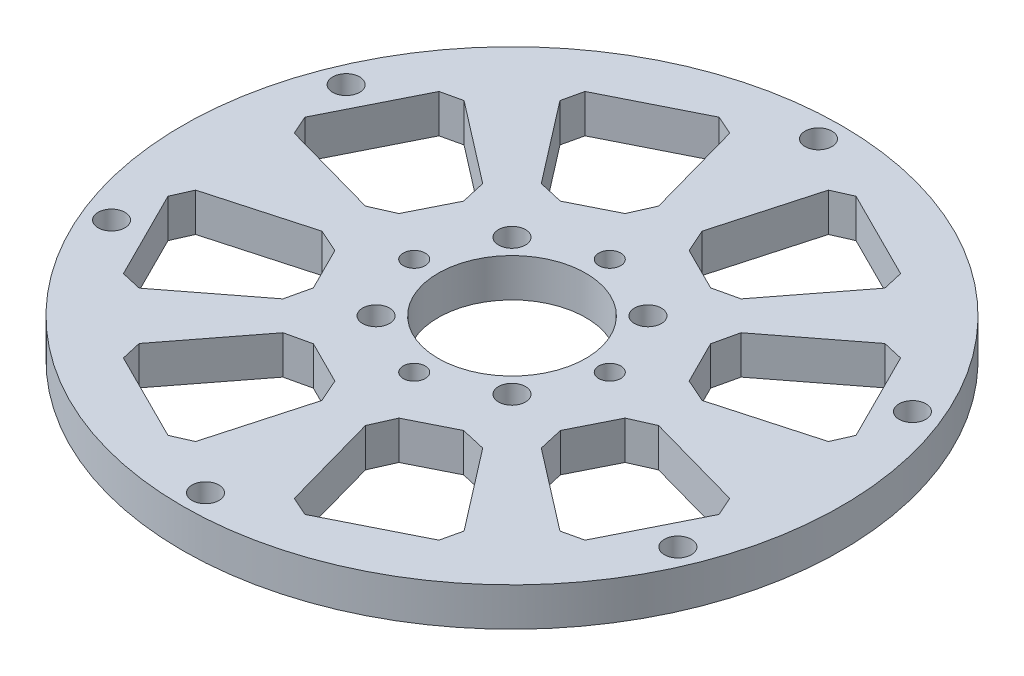
SolidWorks part; units mm, degrees
ref_plane "Front Plane" through (0, 0, 0) normal (0, 0, 1) x (1, 0, 0)
ref_plane "Top Plane" through (0, 0, 0) normal (0, 1, 0) x (1, 0, 0)
ref_plane "Right Plane" through (0, 0, 0) normal (1, 0, 0) x (0, 0, -1)
sketch "Sketch1" plane through (0, 0, 0) normal (0, 1, 0) x (1, 0, 0)
  circle A0 centre (0, 0) radius 60
  dimension "D1" = 120
extrude "Boss-Extrude1" add sketch "Sketch1" along normal blind 7
sketch "Sketch5" plane through (0, 0, 0) normal (0, 1, 0) x (1, 0, 0)
  line L0 (-82.4479, 0) -> (103.3295, 0) construction
  line L1 (0, 67.0321) -> (0, -75.2071) construction
  line L2 (0, 0) -> (-68.1881, 68.1881) construction
  line L3 (-12.4689, 50.1671) -> (-28.7242, 42.0224)
  line L4 (-29.5753, 38.302) -> (-18.1867, 23.5207)
  line L5 (-13.6736, 22.4881) -> (-5.8319, 26.4172)
  line L6 (-3.9571, 30.6504) -> (-8.9793, 48.6217)
  line L7 (-22.4881, 13.6736) -> (-26.4172, 5.8319)
  line L8 (-30.6504, 3.9571) -> (-48.6217, 8.9793)
  line L9 (-38.302, 29.5753) -> (-23.5207, 18.1867)
  line L10 (-50.1671, 12.4689) -> (-42.0224, 28.7242)
  line L11 (22.4881, 13.6736) -> (26.4172, 5.8319)
  line L12 (38.302, 29.5753) -> (23.5207, 18.1867)
  line L13 (50.1671, 12.4689) -> (42.0224, 28.7242)
  line L14 (30.6504, 3.9571) -> (48.6217, 8.9793)
  line L15 (13.6736, 22.4881) -> (5.8319, 26.4172)
  line L16 (29.5753, 38.302) -> (18.1867, 23.5207)
  line L17 (3.9571, 30.6504) -> (8.9793, 48.6217)
  line L18 (12.4689, 50.1671) -> (28.7242, 42.0224)
  line L19 (22.4881, -13.6736) -> (26.4172, -5.8319)
  line L20 (30.6504, -3.9571) -> (48.6217, -8.9793)
  line L21 (50.1671, -12.4689) -> (42.0224, -28.7242)
  line L22 (38.302, -29.5753) -> (23.5207, -18.1867)
  line L23 (13.6736, -22.4881) -> (5.8319, -26.4172)
  line L24 (29.5753, -38.302) -> (18.1867, -23.5207)
  line L25 (12.4689, -50.1671) -> (28.7242, -42.0224)
  line L26 (3.9571, -30.6504) -> (8.9793, -48.6217)
  line L27 (-13.6736, -22.4881) -> (-5.8319, -26.4172)
  line L28 (-3.9571, -30.6504) -> (-8.9793, -48.6217)
  line L29 (-12.4689, -50.1671) -> (-28.7242, -42.0224)
  line L30 (-29.5753, -38.302) -> (-18.1867, -23.5207)
  line L31 (-22.4881, -13.6736) -> (-26.4172, -5.8319)
  line L32 (-38.302, -29.5753) -> (-23.5207, -18.1867)
  line L33 (-50.1671, -12.4689) -> (-42.0224, -28.7242)
  line L34 (-30.6504, -3.9571) -> (-48.6217, -8.9793)
  line L35 (-8.9793, 48.6217) -> (-12.4689, 50.1671)
  line L36 (-5.8319, 26.4172) -> (-3.9571, 30.6504)
  line L37 (-18.1867, 23.5207) -> (-13.6736, 22.4881)
  line L38 (-28.7242, 42.0224) -> (-29.5753, 38.302)
  line L39 (-42.0224, 28.7242) -> (-38.302, 29.5753)
  line L40 (-48.6217, 8.9793) -> (-50.1671, 12.4689)
  line L41 (-26.4172, 5.8319) -> (-30.6504, 3.9571)
  line L42 (-23.5207, 18.1867) -> (-22.4881, 13.6736)
  line L43 (-48.6217, -8.9793) -> (-50.1671, -12.4689)
  line L44 (-26.4172, -5.8319) -> (-30.6504, -3.9571)
  line L45 (-23.5207, -18.1867) -> (-22.4881, -13.6736)
  line L46 (-42.0224, -28.7242) -> (-38.302, -29.5753)
  line L47 (-28.7242, -42.0224) -> (-29.5753, -38.302)
  line L48 (-18.1867, -23.5207) -> (-13.6736, -22.4881)
  line L49 (-5.8319, -26.4172) -> (-3.9571, -30.6504)
  line L50 (-8.9793, -48.6217) -> (-12.4689, -50.1671)
  line L51 (8.9793, -48.6217) -> (12.4689, -50.1671)
  line L52 (28.7242, -42.0224) -> (29.5753, -38.302)
  line L53 (18.1867, -23.5207) -> (13.6736, -22.4881)
  line L54 (5.8319, -26.4172) -> (3.9571, -30.6504)
  line L55 (23.5207, -18.1867) -> (22.4881, -13.6736)
  line L56 (26.4172, -5.8319) -> (30.6504, -3.9571)
  line L57 (48.6217, -8.9793) -> (50.1671, -12.4689)
  line L58 (42.0224, -28.7242) -> (38.302, -29.5753)
  line L59 (48.6217, 8.9793) -> (50.1671, 12.4689)
  line L60 (26.4172, 5.8319) -> (30.6504, 3.9571)
  line L61 (23.5207, 18.1867) -> (22.4881, 13.6736)
  line L62 (42.0224, 28.7242) -> (38.302, 29.5753)
  line L63 (28.7242, 42.0224) -> (29.5753, 38.302)
  line L64 (8.9793, 48.6217) -> (12.4689, 50.1671)
  line L65 (5.8319, 26.4172) -> (3.9571, 30.6504)
  line L66 (18.1867, 23.5207) -> (13.6736, 22.4881)
  point P7 (-9.7868, 51.511)
  point P8 (-31.4063, 40.6784)
  point P9 (-21.1442, 16.3557)
  point P11 (-27.7611, 3.1497)
  point P12 (-16.3557, 21.1442)
  point P13 (-51.511, 9.7868)
  point P14 (-3.1497, 27.7611)
  point P15 (-40.6784, 31.4063)
  point P17 (21.1442, 16.3557)
  point P18 (27.7611, 3.1497)
  point P19 (40.6784, 31.4063)
  point P20 (51.511, 9.7868)
  point P21 (16.3557, 21.1442)
  point P22 (3.1497, 27.7611)
  point P23 (31.4063, 40.6784)
  point P24 (9.7868, 51.511)
  point P25 (21.1442, -16.3557)
  point P26 (27.7611, -3.1497)
  point P27 (51.511, -9.7868)
  point P28 (40.6784, -31.4063)
  point P29 (16.3557, -21.1442)
  point P30 (3.1497, -27.7611)
  point P31 (31.4063, -40.6784)
  point P32 (9.7868, -51.511)
  point P33 (-16.3557, -21.1442)
  point P34 (-3.1497, -27.7611)
  point P35 (-9.7868, -51.511)
  point P36 (-31.4063, -40.6784)
  point P37 (-21.1442, -16.3557)
  point P38 (-27.7611, -3.1497)
  point P39 (-40.6784, -31.4063)
  point P40 (-51.511, -9.7868)
extrude "Cut-Extrude1" cut sketch "Sketch5" against normal blind 20 and the other way through all from offset 0
sketch "Sketch7" plane through (0, 7, 0) normal (0, 1, 0) x (1, 0, 0)
  line L0 (0, 72.965) -> (0, -77.1719) construction
  line L1 (-76.625, 0) -> (90.7777, 0) construction
  circle A0 centre (0, 0) radius 13.4429
extrude "Cut-Extrude2" cut sketch "Sketch7" against normal blind 20 from offset 0
sketch "Sketch9" plane through (0, 0, 0) normal (0, 1, 0) x (1, 0, 0)
  line L0 (-86.0022, 0) -> (100.2446, 0) construction
  line L1 (0, 64.7482) -> (0, -78.9906) construction
  circle A0 centre (0, 17.8) radius 3.5
  circle A2 centre (17.8, 0) radius 3.5
  circle A3 centre (0, -17.8) radius 3.5
  circle A4 centre (-17.8, 0) radius 3.5
extrude "Cut-Extrude3" cut sketch "Sketch9" against normal blind 2 and the other way blind 4
sketch "Sketch13" plane through (0, 0, 0) normal (0, -1, 0) x (-1, 0, 0)
  line L0 (0, -54.6689) -> (0, 78.7715) construction
  line L1 (94.4381, 0) -> (-128.6199, 0) construction
  circle A0 centre (0, -17.8) radius 2
  circle A1 centre (-17.8, 0) radius 2
  circle A2 centre (0, 17.8) radius 2
  circle A3 centre (17.8, 0) radius 2
extrude "Cut-Extrude4" cut sketch "Sketch13" against normal through all
sketch "Sketch14" plane through (0, 0, 0) normal (0, -1, 0) x (-1, 0, 0)
  line L0 (0, -82.8251) -> (0, 72.0178) construction
  line L1 (69.3653, 0) -> (-89.0077, 0) construction
  line L2 (0, 0) -> (54.0642, -54.0642) construction
  line L3 (54.0642, -54.0642) -> (-57.8715, 57.8715) construction
  line L4 (0, 0) -> (-54.0642, -54.0642) construction
  line L5 (-54.0642, -54.0642) -> (54.0642, 54.0642) construction
  circle A0 centre (12.3744, -12.3744) radius 3
  circle A1 centre (-12.3744, -12.3744) radius 3
  circle A3 centre (0, 0) radius 13.4429 construction
  circle A4 centre (-12.3744, 12.3744) radius 3
  circle A5 centre (12.3744, 12.3744) radius 3
  dimension "D1" = 6
  dimension "D2" = 6
  dimension "D3" = 17.5
  dimension "D4" = 17.5
extrude "Cut-Extrude5" cut sketch "Sketch14" against normal blind 3 from surface at 0 starting at face at (0, 0, -14.3)
sketch "Sketch15" plane through (0, 3, 0) normal (0, -1, 0) x (-1, 0, 0)
  circle A0 centre (-12.3744, -12.3744) radius 2.45
  circle A1 centre (12.3744, -12.3744) radius 2.45
  circle A2 centre (12.3744, 12.3744) radius 2.45
  circle A3 centre (-12.3744, 12.3744) radius 2.45
  dimension "D1" = 4.9
extrude "Cut-Extrude6" cut sketch "Sketch15" against normal through all
sketch "Sketch16" plane through (0, 0, 0) normal (0, -1, 0) x (-1, 0, 0)
  line L0 (0, -68.9094) -> (0, 74.0362) construction
  line L1 (87.03, 0) -> (-98.0355, 0) construction
  line L2 (0, 0) -> (-59.0463, 59.0463) construction
  line L3 (0, 0) -> (-124.4425, 51.5458) construction
  circle A0 centre (-51.5525, 21.3537) radius 3
  circle A1 centre (0, 0) radius 60 construction
  circle A2 centre (-51.5525, -21.3537) radius 3
  circle A3 centre (51.5525, 21.3537) radius 3
  circle A4 centre (51.5525, -21.3537) radius 3
  circle A5 centre (0, 55.8) radius 3
  circle A6 centre (0, -55.8) radius 3
  dimension "D3" = 6
  dimension "D5" = 6
  dimension "D6" = 55.8
  dimension "D1" = 45
  dimension "D2" = 22.5
  dimension "D4" = 55.8
extrude "Cut-Extrude7" cut sketch "Sketch16" against normal blind 3 from surface at 0 starting at face at (-12.3744, 0, -9.3744)
sketch "Sketch17" plane through (0, 0, 0) normal (0, -1, 0) x (1, 0, 0)
  line L0 (-79.4288, 0) -> (98.9665, 0) construction
  line L1 (0, 76.5146) -> (0, -96.0771) construction
  circle A0 centre (-51.5525, 21.3537) radius 2.45
  circle A1 centre (-51.5525, -21.3537) radius 2.45
  circle A2 centre (51.5525, -21.3537) radius 2.45
  circle A3 centre (51.5525, 21.3537) radius 2.45
  circle A4 centre (0, -55.8) radius 2.45
  circle A5 centre (0, 55.8) radius 2.45
  dimension "D1" = 4.9
  dimension "D2" = 4.9
extrude "Cut-Extrude8" cut sketch "Sketch17" against normal through all
sketch "Sketch18" plane through (0, 0, 0) normal (0, -1, 0) x (1, 0, 0)
  line L0 (0, 48.1138) -> (0, 35.3321) construction
  line L1 (3.004, 48.1138) -> (3.004, 35.3321)
  line L2 (-3.004, 48.1138) -> (-3.004, 35.3321)
  line L3 (-98.5188, 0) -> (117.4911, 0) construction
  line L4 (0, -48.1138) -> (0, -35.3321) construction
  line L5 (3.004, -48.1138) -> (3.004, -35.3321)
  line L6 (-3.004, -48.1138) -> (-3.004, -35.3321)
  arc A0 (3.004, 48.1138) -> (-3.004, 48.1138) centre (0, 48.1138) ccw
  arc A1 (-3.004, 35.3321) -> (3.004, 35.3321) centre (0, 35.3321) ccw
  arc A2 (3.004, -48.1138) -> (-3.004, -48.1138) centre (0, -48.1138) cw
  arc A3 (-3.004, -35.3321) -> (3.004, -35.3321) centre (0, -35.3321) cw
  point P3 (0, 41.723)
  point P12 (0, -41.723)
extrude "Cut-Extrude9" cut sketch "Sketch18" against normal blind 1 from surface at 0 starting at face at (0, 0, 58.8)
fillet "Fillet2" radius 0.005 8 edges at (3.004, 0, 41.723) (0, 0, 51.1178) (0, 0, 32.3281) (-3.004, 0, 41.723) (-3.004, 1, 41.723) (0, 1, 51.1178) (3.004, 1, 41.723) (0, 1, 32.3281)
